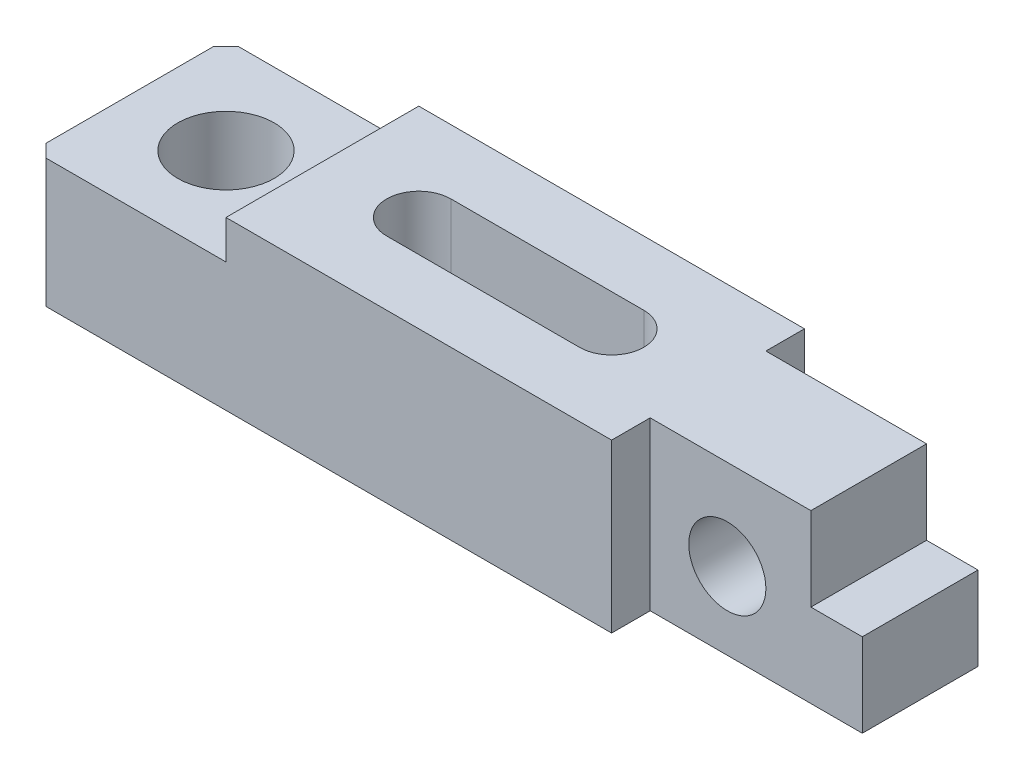
SolidWorks part; units mm, degrees
ref_plane "Piano frontale" through (0, 0, 0) normal (0, 0, 1) x (1, 0, 0)
ref_plane "Piano superiore" through (0, 0, 0) normal (0, 1, 0) x (1, 0, 0)
ref_plane "Piano destro" through (0, 0, 0) normal (1, 0, 0) x (0, 0, -1)
sketch "Schizzo2" plane through (0, 0, 0) normal (0, 0, 1) x (1, 0, 0)
  line L0 (0, 0) -> (123, 0)
  line L1 (123, 0) -> (123, 13)
  line L2 (123, 13) -> (115, 13)
  line L3 (115, 13) -> (115, 26)
  line L4 (115, 26) -> (30, 26)
  line L5 (30, 26) -> (30, 20)
  line L6 (30, 20) -> (0, 20)
  line L7 (0, 20) -> (0, 0)
  point P6 (0, 0)
  dimension "D1" = 123
  dimension "D2" = 30
  dimension "D3" = 8
  dimension "D4" = 6
  dimension "D5" = 26
  dimension "D6" = 13
extrude "Estrusione-Estrusione1" add sketch "Schizzo2" along normal mid plane 30
sketch "Schizzo3" plane through (0, 26, 0) normal (0, 1, 0) x (1, 0, 0)
  line L0 (30, 0) -> (90, 0) construction
  line L1 (30, -15) -> (30, 15) construction
  line L2 (90, -15) -> (90, -9)
  line L3 (115, -15) -> (30, -15) construction
  line L4 (90, -9) -> (123, -9)
  line L5 (123, -15) -> (123, 15) construction
  line L6 (123, -9) -> (123, -15)
  line L7 (123, -15) -> (90, -15)
  line L8 (123, 9) -> (123, 15)
  line L9 (90, 15) -> (90, 9)
  line L10 (90, 9) -> (123, 9)
  line L11 (123, 15) -> (90, 15)
  dimension "D1" = 33
  dimension "D2" = 6
extrude "Taglio-Estrusione1" cut sketch "Schizzo3" against normal through all
sketch "Schizzo4" plane through (0, 26, 0) normal (0, 1, 0) x (1, 0, 0)
  line L0 (45, 0) -> (75, 0) construction
  line L2 (45, 5) -> (75, 5)
  line L3 (45, -5) -> (75, -5)
  line L4 (30, -15) -> (30, 15) construction
  line L5 (90, 15) -> (90, 9) construction
  arc A0 (45, 5) -> (45, -5) centre (45, 0) ccw
  arc A1 (75, -5) -> (75, 5) centre (75, 0) ccw
  point P2 (60, 0)
  dimension "D1" = 15
  dimension "D2" = 15
  dimension "D3" = 10
extrude "Taglio-Estrusione2" cut sketch "Schizzo4" against normal through all
hole_wizard "Foro Ø15.0 (15)-2" positions "Schizzo8" profile "Schizzo9" hole size "Ø15.0" standard "ISO" end condition through all
sketch "Schizzo8" plane through (0, 20, 0) normal (0, 1, 0) x (1, 0, 0)
  line L0 (0, 15) -> (30, -15) construction
  point P6 (15, 0)
sketch "Schizzo9" plane through (15, 20, 0) normal (1, 0, 0) x (0, 0, 1)
  line L0 (0, 0) -> (0, 20)
  line L1 (0, 20) -> (7.5, 20)
  line L2 (7.5, 20) -> (7.5, 0)
  line L5 (7.5, 0) -> (0, 0)
  line L11 (0, -6.35) -> (0, 107.95) construction
  dimension "Thru Hole Dia." = 15
  dimension "Thru Hole Depth" = 20
hole_wizard "Foro Ø12.0 (12)-1" positions "Schizzo10" profile "Schizzo11" hole size "Ø12.0" standard "ISO" end condition up to next
sketch "Schizzo10" plane through (0, 0, 9) normal (0, 0, 1) x (1, 0, 0)
  line L0 (123, 0) -> (90, 0) construction
  line L1 (123, 0) -> (123, 13) construction
  point P0 (102, 12)
  dimension "D1" = 12
  dimension "D2" = 21
sketch "Schizzo11" plane through (102, 12, 9) normal (1, 0, 0) x (0, -1, 0)
  line L0 (0, 0) -> (0, 18)
  line L1 (0, 18) -> (6, 18)
  line L2 (6, 18) -> (6, 0)
  line L5 (6, 0) -> (0, 0)
  line L11 (0, -6.35) -> (0, 107.95) construction
  dimension "Thru Hole Dia." = 12
  dimension "Thru Hole Depth" = 18
chamfer "Smusso1" distance 2 angle 45 2 edges at (0, 10, -15) (0, 10, 15)
